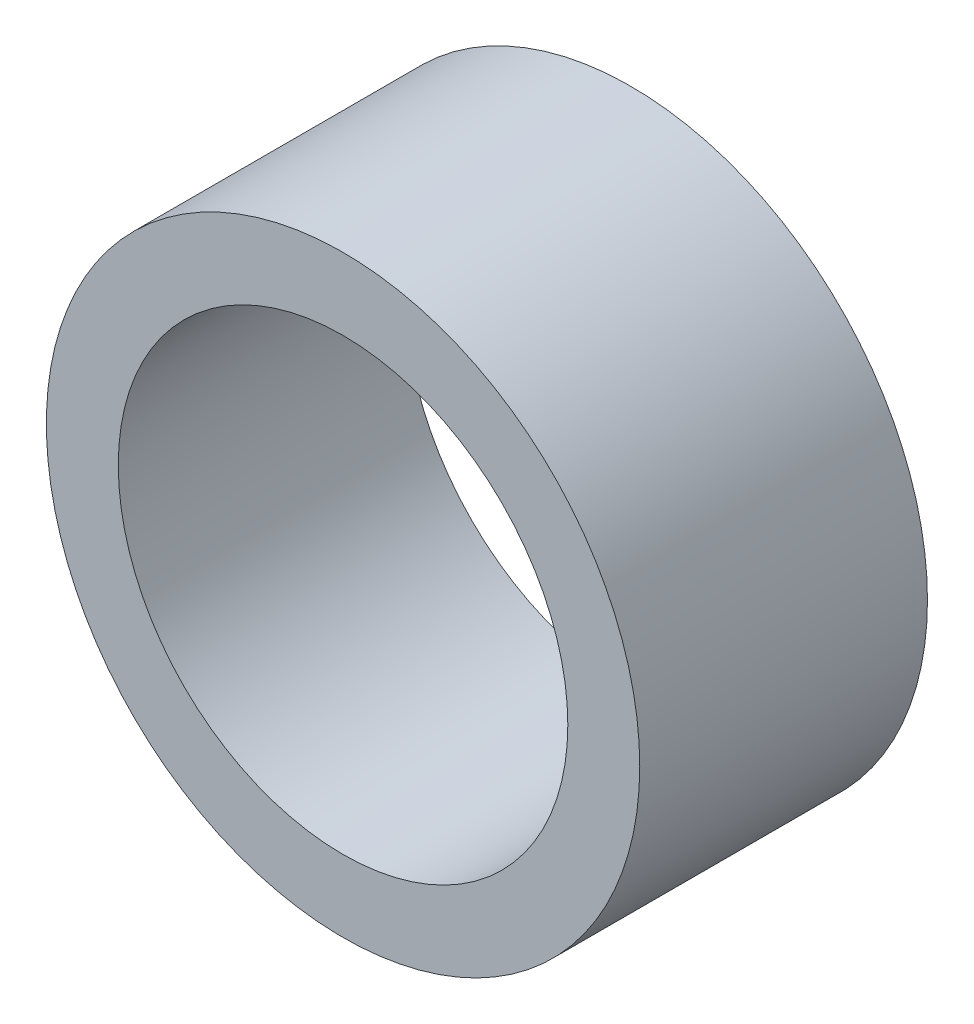
SolidWorks part; units mm, degrees
ref_plane "前视基准面" through (0, 0, 0) normal (0, 0, 1) x (1, 0, 0)
ref_plane "上视基准面" through (0, 0, 0) normal (0, 1, 0) x (1, 0, 0)
ref_plane "右视基准面" through (0, 0, 0) normal (1, 0, 0) x (0, 0, -1)
sketch "草图1" plane through (0, 0, 0) normal (0, 0, 1) x (1, 0, 0)
  circle A0 centre (0, 0) radius 16.5
  circle A1 centre (0, 0) radius 12.5
  dimension "D1" = 33
  dimension "D2" = 25
extrude "凸台-拉伸1" add sketch "草图1" along normal blind 16
